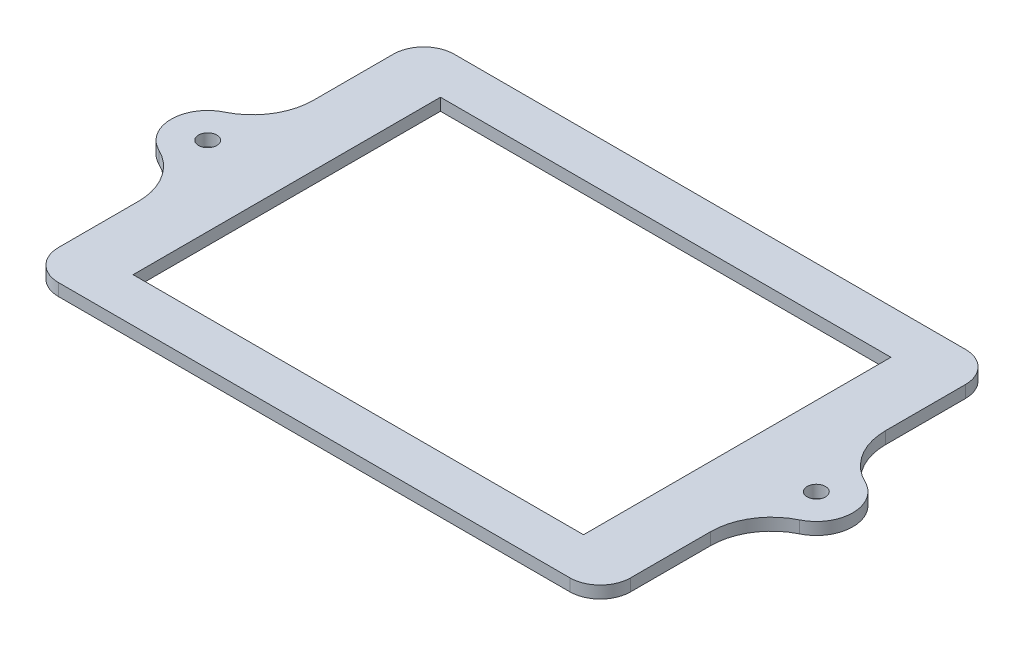
SolidWorks part; units mm, degrees
material "ABS"
ref_plane "Front Plane" through (0, 0, 0) normal (0, 0, 1) x (1, 0, 0)
ref_plane "Top Plane" through (0, 0, 0) normal (0, 1, 0) x (1, 0, 0)
ref_plane "Right Plane" through (0, 0, 0) normal (1, 0, 0) x (0, 0, -1)
sketch "Sketch2" plane through (0, 0, 0) normal (0, 1, 0) x (1, 0, 0)
  line L0 (0, 32.5) -> (0, 25.25) construction
  line L1 (-37, 25.25) -> (37, 25.25)
  line L2 (-37, 25.25) -> (-37, -25.25)
  line L3 (-37, -25.25) -> (37, -25.25)
  line L4 (37, 25.25) -> (37, -25.25)
  line L5 (-47, 32.5) -> (47, 32.5)
  line L6 (-47, 32.5) -> (-47, 5.1962)
  line L7 (-47, -32.5) -> (47, -32.5)
  line L8 (47, 32.5) -> (47, 5.1962)
  line L9 (0, 25.25) -> (0, 0) construction
  line L10 (0, 0) -> (0, -25.25) construction
  line L11 (0, -25.25) -> (0, -32.5) construction
  line L12 (-50, 0) -> (0, 0) construction
  line L13 (0, 0) -> (50, 0) construction
  line L14 (-47, -5.1962) -> (-47, -32.5)
  line L15 (47, -5.1962) -> (47, -32.5)
  arc A0 (-47, 5.1962) -> (-47, -5.1962) centre (-50, 0) ccw
  arc A1 (47, -5.1962) -> (47, 5.1962) centre (50, 0) ccw
  circle A2 centre (-50, 0) radius 1.5
  circle A3 centre (50, 0) radius 1.5
  dimension "D7" = 12
  dimension "D9" = 3
  dimension "D1" = 65
  dimension "D2" = 7.25
  dimension "D3" = 94
  dimension "D5" = 50.5
  dimension "D6" = 74
  dimension "D8" = 100
extrude "Boss-Extrude1" add sketch "Sketch2" along normal blind 2
fillet "Fillet1" radius 5 4 edges at (-47, 1, -32.5) (47, 1, -32.5) (47, 1, 32.5) (-47, 1, 32.5)
fillet "Fillet2" radius 10 4 edges at (-47, 1, -5.1962) (-47, 1, 5.1962) (47, 1, -5.1962) (47, 1, 5.1962)
